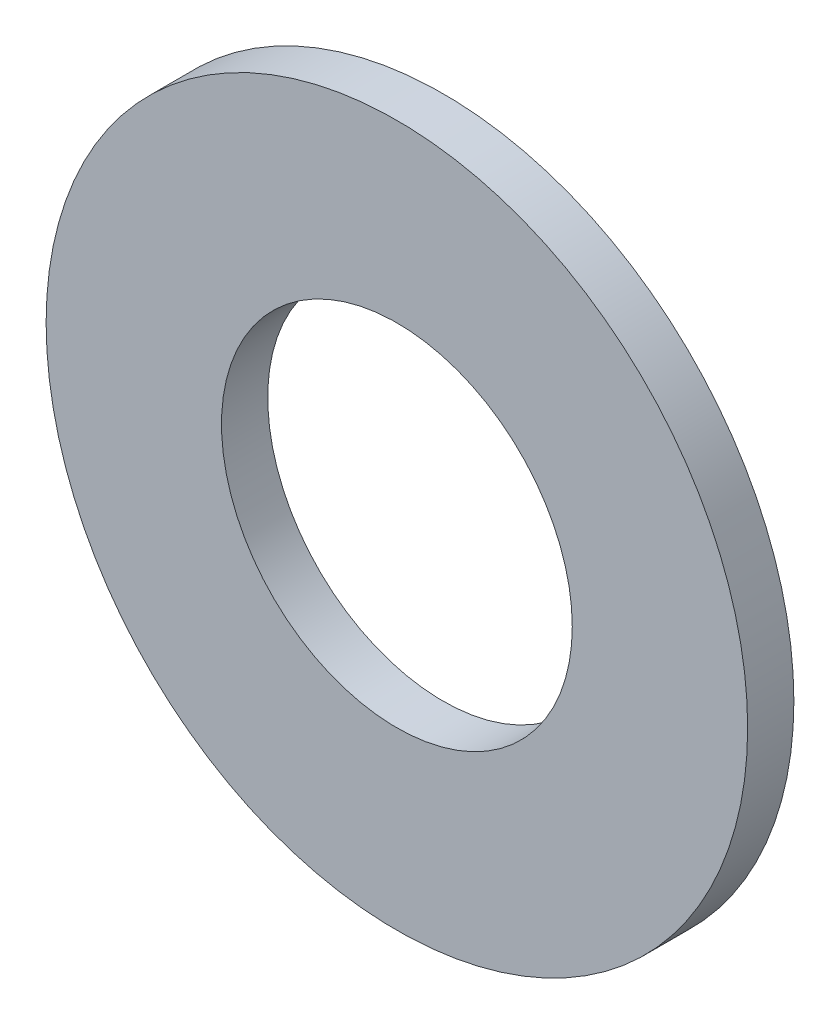
SolidWorks part; units mm, degrees
material "Cast Alloy Steel"
ref_plane "Front Plane" through (0, 0, 0) normal (0, 0, 1) x (1, 0, 0)
ref_plane "Top Plane" through (0, 0, 0) normal (0, 1, 0) x (1, 0, 0)
ref_plane "Right Plane" through (0, 0, 0) normal (1, 0, 0) x (0, 0, -1)
sketch "Sketch1" plane through (0, 0, 0) normal (0, 0, 1) x (1, 0, 0)
  circle A0 centre (0, 0) radius 6.7469
  circle A1 centre (0, 0) radius 13.4938
  dimension "ID" = 13.4937
  dimension "OD" = 26.9875
extrude "Extrude1" add sketch "Sketch1" against normal blind 1.778
